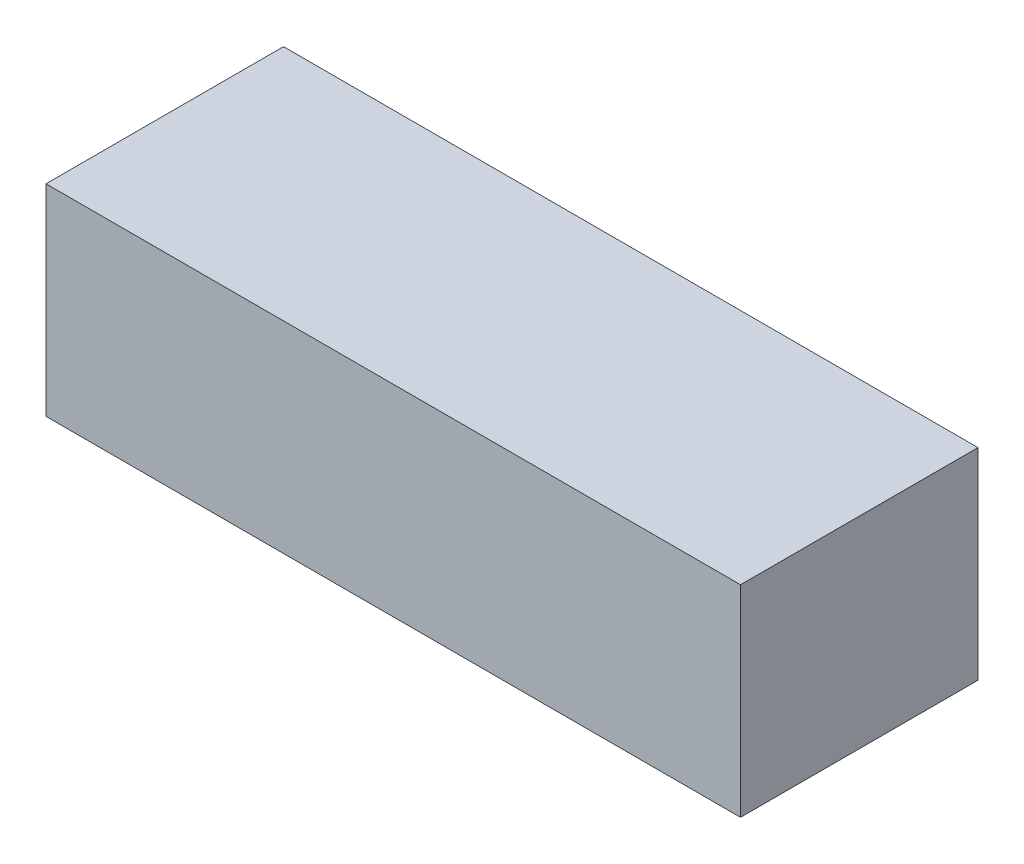
SolidWorks part; units mm, degrees
ref_plane "前基準面" through (0, 0, 0) normal (0, 0, 1) x (1, 0, 0)
ref_plane "上基準面" through (0, 0, 0) normal (0, 1, 0) x (1, 0, 0)
ref_plane "右基準面" through (0, 0, 0) normal (1, 0, 0) x (0, 0, -1)
sketch "草圖1" plane through (0, 0, 0) normal (0, 1, 0) x (1, 0, 0)
  line L1 (-32.75, 11.2) -> (32.75, 11.2)
  line L2 (-32.75, 11.2) -> (-32.75, -11.2)
  line L3 (-32.75, -11.2) -> (32.75, -11.2)
  line L4 (32.75, 11.2) -> (32.75, -11.2)
  line L5 (-32.75, 11.2) -> (32.75, -11.2) construction
  line L6 (-32.75, -11.2) -> (32.75, 11.2) construction
  point P0 (0, 0)
  dimension "D1" = 65.5
  dimension "D2" = 22.4
extrude "填料-伸長1" add sketch "草圖1" along normal blind 19
